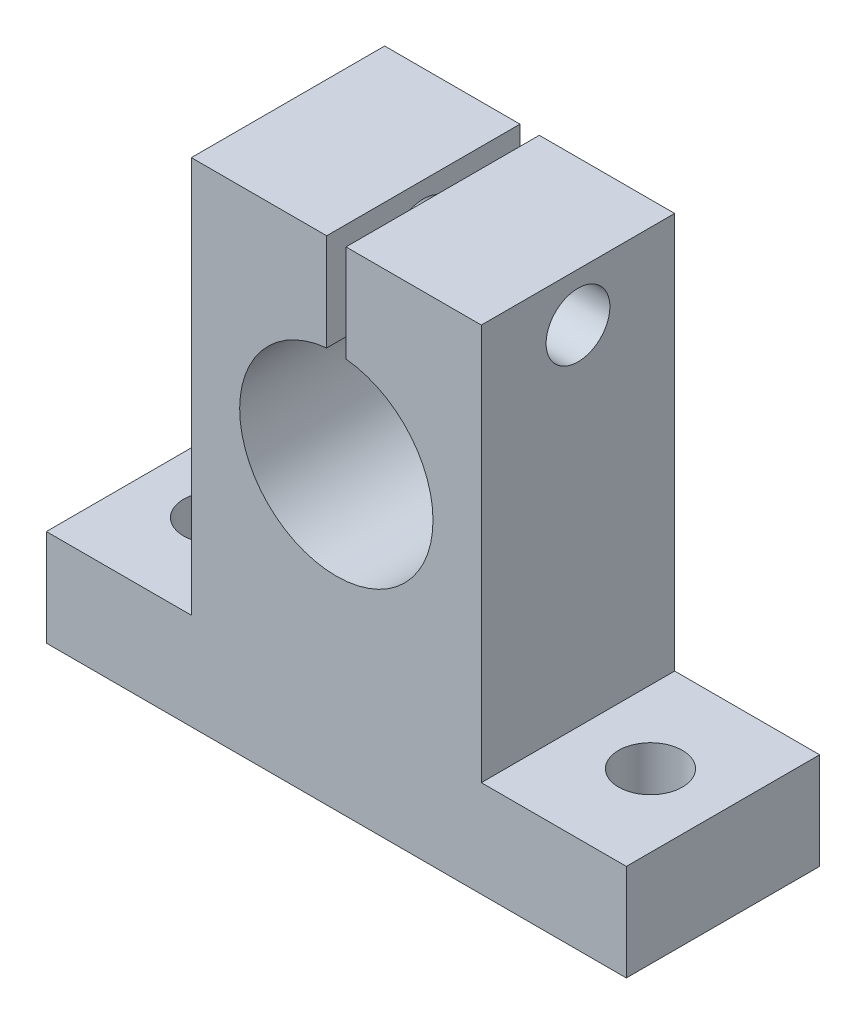
SolidWorks part; units mm, degrees
ref_plane "Front Plane" through (0, 0, 0) normal (0, 0, 1) x (1, 0, 0)
ref_plane "Top Plane" through (0, 0, 0) normal (0, 1, 0) x (1, 0, 0)
ref_plane "Right Plane" through (0, 0, 0) normal (1, 0, 0) x (0, 0, -1)
sketch "Sketch2" plane through (0, 0, 0) normal (0, 0, 1) x (1, 0, 0)
  line L0 (45, 10) -> (60, 10)
  line L1 (0, 0) -> (60, 0)
  line L2 (0, 0) -> (0, 10)
  line L3 (15, 51) -> (45, 51)
  line L4 (60, 0) -> (60, 10)
  line L5 (0, 10) -> (15, 10)
  line L14 (15, 10) -> (15, 51)
  line L16 (45, 10) -> (45, 51)
extrude "Boss-Extrude1" add sketch "Sketch2" along normal mid plane 20
sketch "Sketch3" plane through (0, 0, 10) normal (0, 0, 1) x (1, 0, 0)
  line L0 (30, 51) -> (30, 0)
  line L1 (45, 51) -> (15, 51) construction
  line L2 (0, 0) -> (60, 0) construction
  line L3 (30, 0) -> (30, 31) construction
  circle A0 centre (30, 31) radius 10
extrude "Cut-Extrude1" cut sketch "Sketch3" against normal blind 26 contours A0
sketch "Sketch9" plane through (0, 10, 0) normal (0, 1, 0) x (1, 0, 0)
  line L0 (0, 0) -> (15, 0) construction
  line L1 (0, -10) -> (0, 10) construction
  line L2 (15, -10) -> (15, 10) construction
  line L3 (7.5, -10) -> (7.5, 10) construction
  line L4 (15, -10) -> (0, -10) construction
  line L5 (15, 10) -> (0, 10) construction
  circle A0 centre (7.5, 0) radius 3.3
extrude "Cut-Extrude2" cut sketch "Sketch9" against normal blind 26
sketch "Sketch10" plane through (0, 10, 0) normal (0, 1, 0) x (1, 0, 0)
  line L0 (45, 0) -> (60, 0) construction
  line L2 (45, -10) -> (45, 10) construction
  line L3 (60, -10) -> (60, 10) construction
  line L4 (52.5, -10) -> (52.5, 10) construction
  line L5 (60, -10) -> (45, -10) construction
  line L6 (60, 10) -> (45, 10) construction
  circle A0 centre (52.5, 0) radius 3.3
extrude "Cut-Extrude3" cut sketch "Sketch10" against normal blind 26 contours A0
sketch "Sketch12" plane through (15, 0, 0) normal (-1, 0, 0) x (0, 0, 1)
  line L0 (0, 51) -> (0, 41) construction
  line L1 (10, 51) -> (-10, 51) construction
  circle A0 centre (0, 46) radius 3.3
extrude "Cut-Extrude5" cut sketch "Sketch12" against normal blind 46
sketch "Sketch14" plane through (0, 0, -10) normal (0, 0, -1) x (-1, 0, 0)
  line L4 (-30.8855, 40.9607) -> (-30.8855, 40.9063)
  line L5 (-29.1117, 40.9605) -> (-29.1117, 40.9063)
  circle A0 centre (-30, 31) radius 10 construction
sketch "Sketch15" plane through (0, 51, 0) normal (0, 1, 0) x (1, 0, 0)
  line L0 (45, 10) -> (15, 10) construction
  line L2 (45, -10) -> (15, -10) construction
  line L3 (45, 0) -> (15, 0) construction
  line L4 (45, -10) -> (45, 10) construction
  line L5 (15, -10) -> (15, 10) construction
  line L6 (30, 0) -> (30, -10) construction
  line L7 (31, -10) -> (29, -10)
  line L8 (31, -10) -> (31, 10)
  line L9 (31, 10) -> (29, 10)
  line L10 (29, -10) -> (29, 10)
extrude "Cut-Extrude7" cut sketch "Sketch15" against normal blind 15
